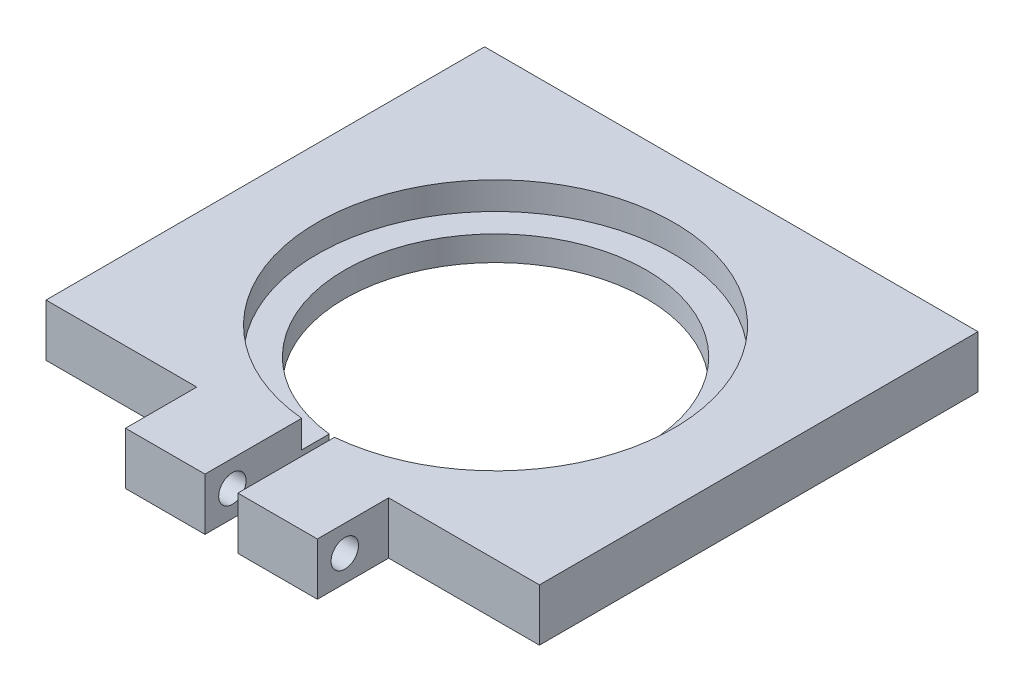
SolidWorks part; units mm, degrees
ref_plane "Plano frontal" through (0, 0, 0) normal (0, 0, 1) x (1, 0, 0)
ref_plane "Plano superior" through (0, 0, 0) normal (0, 1, 0) x (1, 0, 0)
ref_plane "Plano direito" through (0, 0, 0) normal (1, 0, 0) x (0, 0, -1)
sketch "Esboço1" plane through (0, 0, 0) normal (0, 1, 0) x (1, 0, 0)
  line L0 (45, 46.5) -> (-45, -46.5) construction
  line L1 (-45, 46.5) -> (45, 46.5)
  line L2 (-45, 46.5) -> (-45, -46.5)
  line L3 (-45, -46.5) -> (45, -46.5)
  line L4 (45, 46.5) -> (45, -46.5)
  dimension "D1" = 90
  dimension "D2" = 93
extrude "Ressalto-extrusão1" add sketch "Esboço1" along normal blind 9.53 contours L2 L3 L4 L1
sketch "Esboço3" plane through (0, 9.53, 0) normal (0, 1, 0) x (1, 0, 0)
  line L0 (-45, -46.5) -> (45, -46.5) construction
  line L1 (45, 46.5) -> (45, -46.5) construction
  circle A0 centre (0, 3.5) radius 32.51
  dimension "D1" = 65.02
  dimension "D2" = 50
  dimension "D3" = 45
extrude "Corte-extrusão2" cut sketch "Esboço3" against normal blind 5
sketch "Esboço2" plane through (0, 0, -46.5) normal (0, 0, -1) x (-1, 0, 0)
  line L0 (45, 4.765) -> (-45, 4.765) construction
  line L1 (45, 9.53) -> (45, 0) construction
  line L2 (-45, 9.53) -> (-45, 0) construction
  circle A0 centre (-40, 4.765) radius 2.6
  circle A1 centre (-25, 4.765) radius 2.6
  circle A2 centre (25, 4.76) radius 2.6
  circle A3 centre (40, 4.765) radius 2.6
  dimension "D1" = 5
  dimension "D2" = 5
  dimension "D3" = 20
  dimension "D4" = 20
  dimension "D5" = 70
extrude "Corte-extrusão1" cut sketch "Esboço2" against normal blind 19
sketch "Esboço4" plane through (0, 4.53, 0) normal (0, 1, 0) x (1, 0, 0)
  circle A0 centre (0, 3.5) radius 27.5
  dimension "D1" = 55
extrude "Corte-extrusão3" cut sketch "Esboço4" against normal up to next
sketch "Esboço5" plane through (0, 9.53, 0) normal (0, 1, 0) x (1, 0, 0)
  line L0 (0, -46.5) -> (0, -37.4552) construction
  line L1 (45, -46.5) -> (17.5, -46.5)
  line L2 (45, -46.5) -> (45, -33.5)
  line L3 (45, -33.5) -> (17.5, -33.5)
  line L4 (17.5, -46.5) -> (17.5, -33.5)
  line L5 (-45, -46.5) -> (-17.5, -46.5)
  line L6 (-45, -46.5) -> (-45, -33.5)
  line L7 (-45, -33.5) -> (-17.5, -33.5)
  line L8 (-17.5, -46.5) -> (-17.5, -33.5)
  line L9 (-45, -46.5) -> (45, -46.5) construction
  dimension "D1" = 17.5
  dimension "D2" = 17.5
  dimension "D3" = 13
  dimension "D4" = 13
extrude "Corte-extrusão4" cut sketch "Esboço5" against normal up to next
sketch "Esboço6" plane through (0, 9.53, 0) normal (0, 1, 0) x (1, 0, 0)
  line L1 (0, 0) -> (0, -46.5) construction
  line L2 (-17.5, -46.5) -> (17.5, -46.5) construction
  line L3 (3, -46.5) -> (-3, -46.5)
  line L4 (3, -46.5) -> (3, -20.3326)
  line L5 (3, -20.3326) -> (-3, -20.3326)
  line L6 (-3, -46.5) -> (-3, -20.3326)
  dimension "D1" = 3
  dimension "D2" = 3
extrude "Corte-extrusão5" cut sketch "Esboço6" against normal up to next
sketch "Esboço7" plane through (-17.5, 0, 0) normal (-1, 0, 0) x (0, 0, 1)
  line L0 (46.5, 9.53) -> (36.5, 0) construction
  line L1 (46.5, 0) -> (33.5, 0) construction
  circle A0 centre (41.5, 4.765) radius 2.5
  dimension "D2" = 5
  dimension "D1" = 10
extrude "Corte-extrusão6" cut sketch "Esboço7" against normal up to surface (35 mm away) up to face at (17.5, 4.765, 40)
